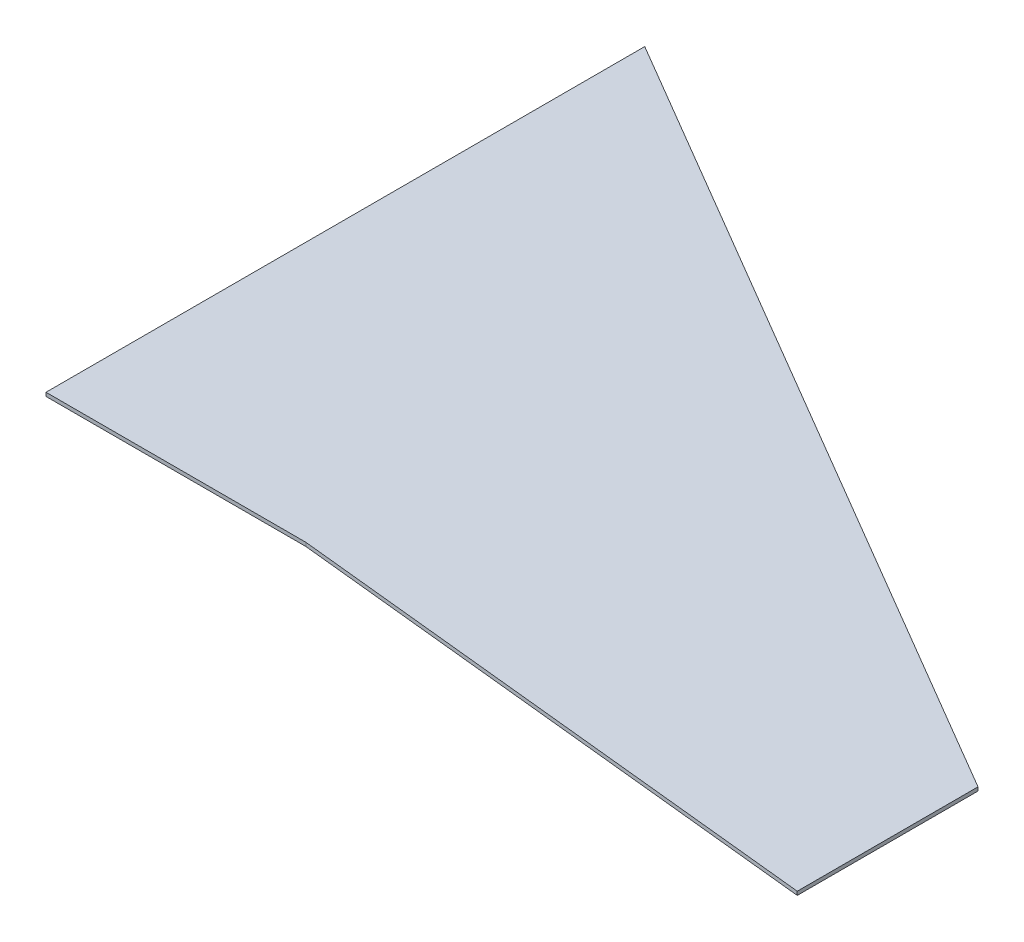
SolidWorks part; units mm, degrees
material "1023 Carbon Steel Sheet (SS)"
ref_plane "Front Plane" through (0, 0, 0) normal (0, 0, 1) x (1, 0, 0)
ref_plane "Top Plane" through (0, 0, 0) normal (0, 1, 0) x (1, 0, 0)
ref_plane "Right Plane" through (0, 0, 0) normal (1, 0, 0) x (0, 0, -1)
sketch "Sketch1" plane through (0, 0, 0) normal (0, 1, 0) x (1, 0, 0)
  line L0 (0, 0) -> (0, 336.55)
  line L1 (0, 336.55) -> (454.025, 69.85)
  line L2 (454.025, 69.85) -> (454.025, -31.75)
  line L3 (454.025, -31.75) -> (146.05, 0)
  line L4 (146.05, 0) -> (0, 0)
  dimension "D1" = 336.55
  dimension "D2" = 146.05
  dimension "D3" = 454.025
  dimension "D4" = 101.6
  dimension "D5" = 31.75
extrude "Boss-Extrude1" add sketch "Sketch1" along normal blind 2.0574
